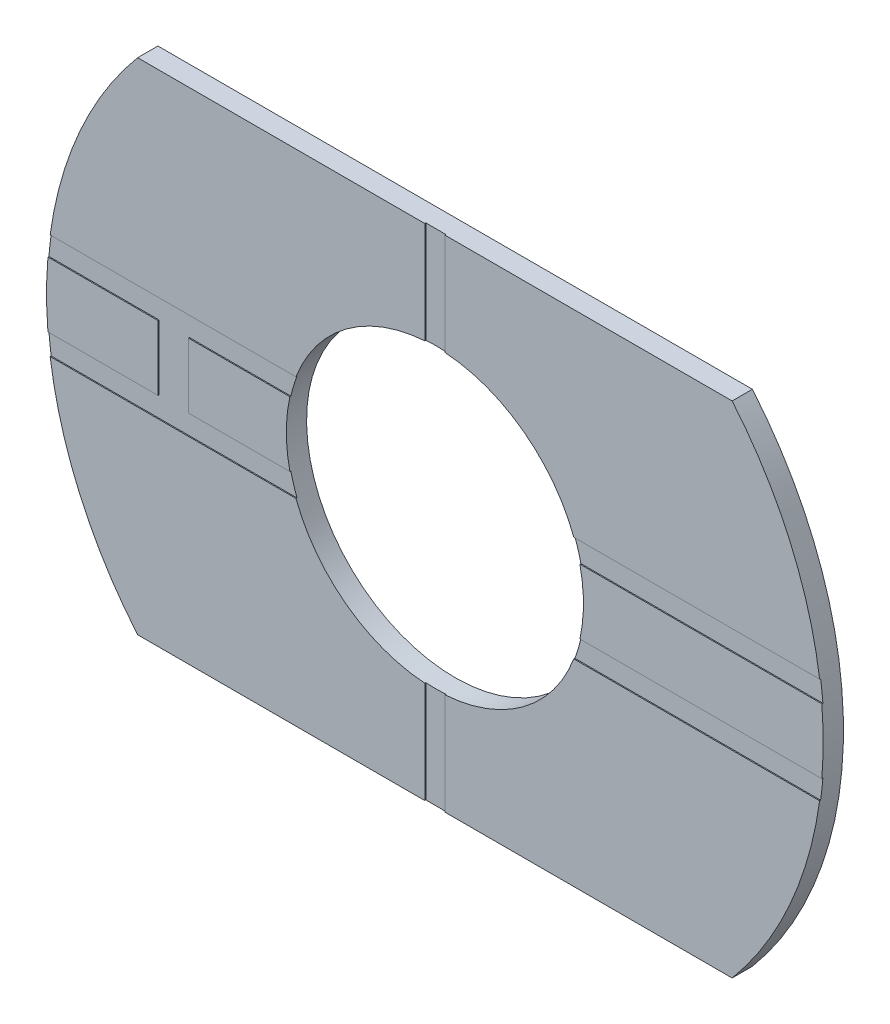
SolidWorks part; units mm, degrees
ref_plane "Спереди" through (0, 0, 0) normal (0, 0, 1) x (1, 0, 0)
ref_plane "Сверху" through (0, 0, 0) normal (0, 1, 0) x (1, 0, 0)
ref_plane "Справа" through (0, 0, 0) normal (1, 0, 0) x (0, 0, -1)
sketch "Эскиз1" plane through (0, 0, 0) normal (0, 0, 1) x (1, 0, 0)
  circle A0 centre (0, 0) radius 57.5
  circle A1 centre (0, 0) radius 22
  dimension "D1" = 44
  dimension "D2" = 115
extrude "Бобышка-Вытянуть1" add sketch "Эскиз1" along normal blind 3
sketch "Эскиз2" plane through (0, 0, 3) normal (0, 0, 1) x (1, 0, 0)
  line L1 (-71.6771, 37) -> (68.8401, 37)
  line L2 (-71.6771, 37) -> (-71.6771, 91.8379)
  line L3 (-71.6771, 91.8379) -> (68.8401, 91.8379)
  line L4 (68.8401, 37) -> (68.8401, 91.8379)
  line L5 (-71.6771, -94.4571) -> (68.8401, -94.4571)
  line L6 (-71.6771, -94.4571) -> (-71.6771, -37)
  line L7 (-71.6771, -37) -> (68.8401, -37)
  line L8 (68.8401, -94.4571) -> (68.8401, -37)
  dimension "D1" = 74
  dimension "D2" = 37
extrude "Вырез-Вытянуть1" cut sketch "Эскиз2" against normal through all
sketch "Эскиз3" plane through (0, 0, 3) normal (0, 0, 1) x (1, 0, 0)
  line L0 (-72.4233, -77.7327) -> (-21.3533, -77.7327) construction
  line L1 (-44.0142, 37) -> (44.0142, 37) construction
  line L2 (-1.5, 37) -> (1.5, 37)
  line L3 (-1.5, 37) -> (-1.5, 7.8)
  line L4 (-1.5, -37) -> (1.5, -37)
  line L5 (1.5, 37) -> (1.5, 7.8)
  line L6 (44.0142, -37) -> (-44.0142, -37) construction
  line L7 (1.5, 4.8) -> (1.5, -4.8)
  line L8 (-72.371, 7.8) -> (-1.5, 7.8)
  line L9 (-72.371, 7.8) -> (-72.371, 4.8)
  line L10 (-72.371, 4.8) -> (-41, 4.8)
  line L11 (63.7438, 7.8) -> (63.7438, 4.8)
  line L12 (65.5822, -4.8) -> (1.5, -4.8)
  line L13 (65.5822, -4.8) -> (65.5822, -7.8)
  line L14 (65.5822, -7.8) -> (1.5, -7.8)
  line L15 (-73.6341, -4.8) -> (-73.6341, -7.8)
  line L17 (-41, 4.8) -> (-41, -4.8)
  line L19 (-36.5, 4.8) -> (-36.5, -4.8)
  line L20 (-1.5, 4.8) -> (-1.5, -4.8)
  line L21 (1.5, 7.8) -> (63.7438, 7.8)
  line L22 (1.5, 4.8) -> (63.7438, 4.8)
  line L23 (-1.5, -4.8) -> (-36.5, -4.8)
  line L24 (-1.5, -7.8) -> (-73.6341, -7.8)
  line L25 (-1.5, -7.8) -> (-1.5, -37)
  line L26 (1.5, -7.8) -> (1.5, -37)
  line L27 (-36.5, 4.8) -> (-1.5, 4.8)
  line L28 (-41, -4.8) -> (-73.6341, -4.8)
  point P18 (-72.371, 4.8)
  dimension "D1" = 3
  dimension "D2" = 1.5
  dimension "D3" = 3
  dimension "D4" = 3
  dimension "D5" = 4.8
  dimension "D6" = 4.8
  dimension "D7" = 35
  dimension "D8" = 4.5
extrude "Вырез-Вытянуть2" cut sketch "Эскиз3" against normal blind 0.15
